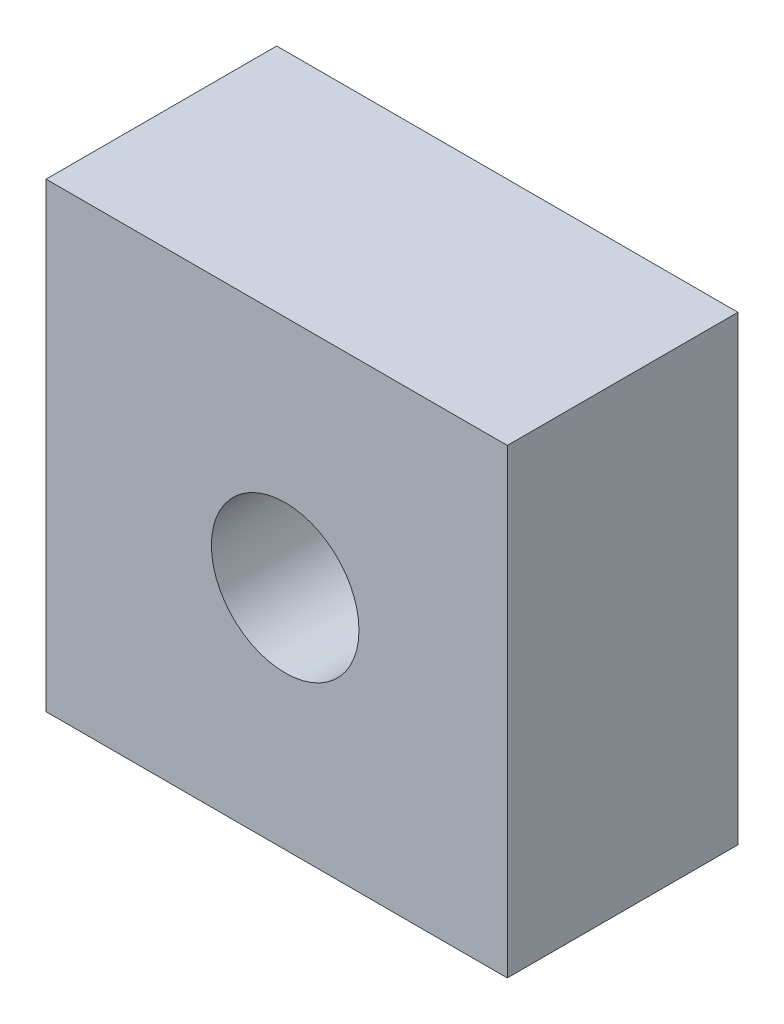
SolidWorks part; units mm, degrees
ref_plane "Front Plane" through (0, 0, 0) normal (0, 0, 1) x (1, 0, 0)
ref_plane "Top Plane" through (0, 0, 0) normal (0, 1, 0) x (1, 0, 0)
ref_plane "Right Plane" through (0, 0, 0) normal (1, 0, 0) x (0, 0, -1)
sketch "Sketch1" plane through (0, 0, 0) normal (0, 1, 0) x (1, 0, 0)
  line L1 (0, 0) -> (100, 0)
  line L2 (0, 0) -> (0, -50)
  line L3 (0, -50) -> (100, -50)
  line L4 (100, 0) -> (100, -50)
  dimension "D1" = 100
  dimension "D2" = 50
extrude "Boss-Extrude1" add sketch "Sketch1" along normal blind 100
sketch "Sketch2" plane through (0, 0, 0) normal (0, 0, -1) x (-1, 0, 0)
  circle A0 centre (-51.8404, 49.1988) radius 16
extrude "Cut-Extrude1" cut sketch "Sketch2" against normal blind 100
